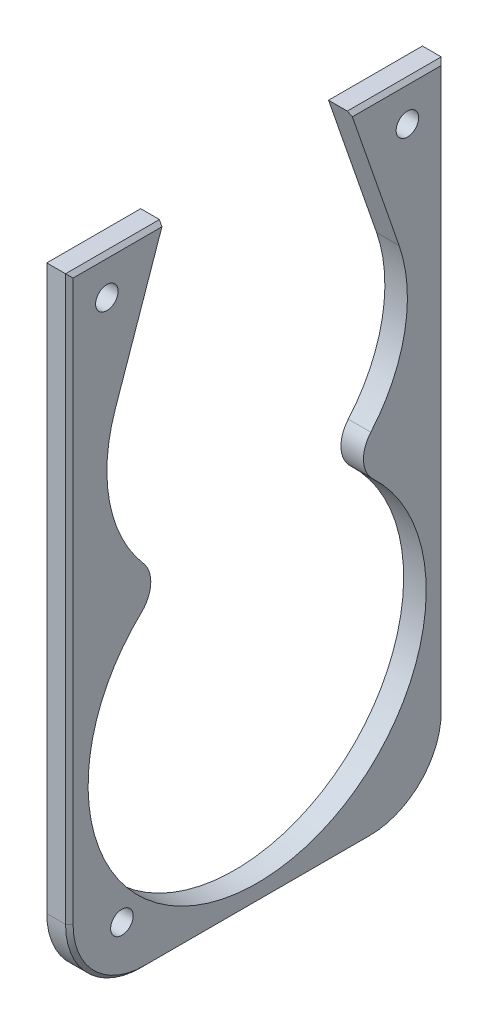
SolidWorks part; units mm, degrees
ref_plane "前视基准面" through (0, 0, 0) normal (0, 0, 1) x (1, 0, 0)
ref_plane "上视基准面" through (0, 0, 0) normal (0, 1, 0) x (1, 0, 0)
ref_plane "右视基准面" through (0, 0, 0) normal (1, 0, 0) x (0, 0, -1)
other "Configuration Table"
sketch "草图1" plane through (0, 0, 0) normal (1, 0, 0) x (0, 0, -1)
  line L1 (-25, 50) -> (25, 50)
  line L2 (-25, 50) -> (-25, -35)
  line L3 (-25, -35) -> (25, -35)
  line L4 (25, 50) -> (25, -35)
  dimension "D1" = 85
  dimension "D2" = 50
  dimension "D3" = 25
  dimension "D4" = 35
extrude "凸台-拉伸1" add sketch "草图1" along normal blind 3
fillet "圆角2" radius 10 2 edges at (1.5, -35, -25) (1.5, -35, 25)
sketch "草图4" plane through (3, 0, 0) normal (1, 0, 0) x (0, 0, -1)
  line L0 (25, 50) -> (-25, 50) construction
  line L1 (-15, -35) -> (15, -35) construction
  line L2 (-25, 50) -> (-25, -25) construction
  circle A0 centre (20, 45) radius 1.5
  circle A1 centre (-20, 45) radius 1.5
  circle A2 centre (-18, -28) radius 1.5
  dimension "D1" = 3
  dimension "D5" = 3
  dimension "D6" = 7
  dimension "D2" = 40
  dimension "D3" = 20
  dimension "D4" = 5
  dimension "D7" = 7
extrude "切除-拉伸1" cut sketch "草图4" against normal blind 3
chamfer "倒角1" distance 0.5 angle 45 6 edges at (3, 12.5, -25) (3, -32.0711, -22.0711) (3, -35, 0) (3, -32.0711, 22.0711) (3, 50, 0) (3, 12.5, 25)
sketch "草图6" plane through (3, 0, 0) normal (1, 0, 0) x (0, 0, -1)
  line L0 (-25, 50) -> (25, 50) construction
  line L1 (-12.5, 50) -> (12.5, 50)
  line L3 (-12.5, 50) -> (-18.8964, 31.5518)
  line L4 (18.8964, 31.5518) -> (12.5, 50)
  arc A0 (-18.8964, 31.5518) -> (18.8964, 31.5518) centre (0, 25) ccw
  dimension "D1" = 25
  dimension "D2" = 40
  dimension "D3" = 25
  dimension "D4" = 12.5
extrude "切除-拉伸3" cut sketch "草图6" against normal blind 3
sketch "草图7" plane through (3, 0, 0) normal (1, 0, 0) x (0, 0, -1)
  circle A0 centre (0, -10) radius 22.5
  dimension "D1" = 10
  dimension "D2" = 45
extrude "切除-拉伸4" cut sketch "草图7" against normal blind 3
fillet "圆角4" radius 4 2 edges at (1.5, 9.0179, 12.0238) (1.5, 9.0179, -12.0238)
